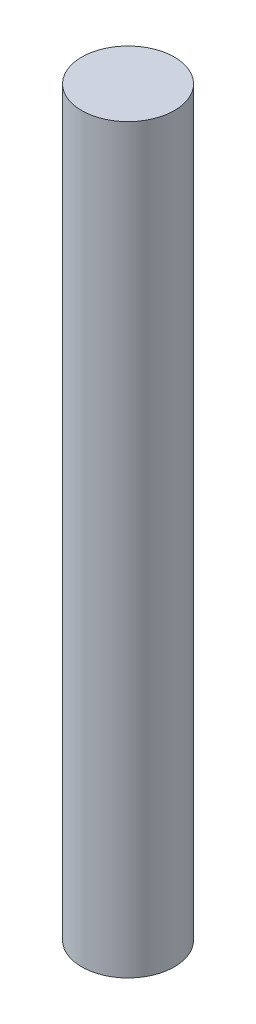
SolidWorks part; units mm, degrees
material "Chrome Stainless Steel"
ref_plane "Front Plane" through (0, 0, 0) normal (0, 0, 1) x (1, 0, 0)
ref_plane "Top Plane" through (0, 0, 0) normal (0, 1, 0) x (1, 0, 0)
ref_plane "Right Plane" through (0, 0, 0) normal (1, 0, 0) x (0, 0, -1)
sketch "Sketch1" plane through (0, 0, 0) normal (0, 1, 0) x (1, 0, 0)
  circle A0 centre (0, 0) radius 9.525
  dimension "D1" = 19.05
extrude "Boss-Extrude1" add sketch "Sketch1" along normal mid plane 152.4
